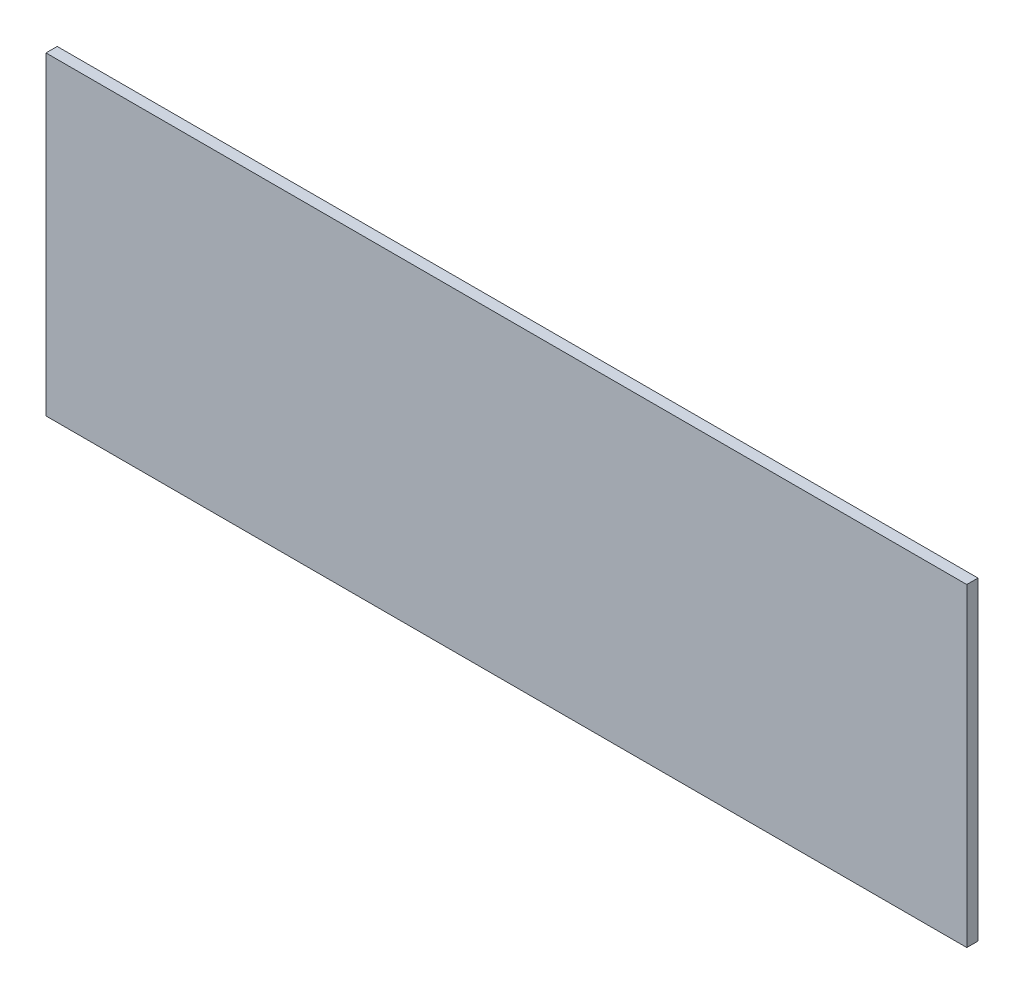
SolidWorks part; units mm, degrees
ref_plane "正面" through (0, 0, 0) normal (0, 0, 1) x (1, 0, 0)
ref_plane "平面" through (0, 0, 0) normal (0, 1, 0) x (1, 0, 0)
ref_plane "右側面" through (0, 0, 0) normal (1, 0, 0) x (0, 0, -1)
sketch "ｽｹｯﾁ1" plane through (0, 0, 0) normal (0, 0, 1) x (1, 0, 0)
  line L1 (-69.2801, 161.5071) -> (340.7199, 161.5071)
  line L2 (-69.2801, 161.5071) -> (-69.2801, 21.5071)
  line L3 (-69.2801, 21.5071) -> (340.7199, 21.5071)
  line L4 (340.7199, 161.5071) -> (340.7199, 21.5071)
  dimension "D1" = 410
  dimension "D3" = 140
extrude "ﾎﾞｽ - 押し出し1" add sketch "ｽｹｯﾁ1" along normal blind 5
